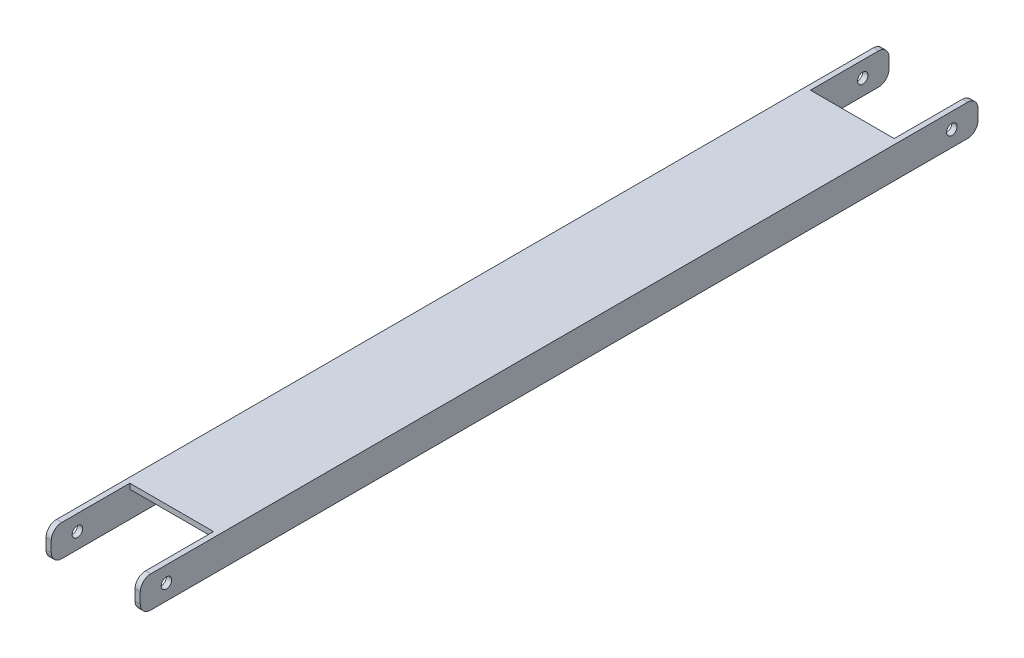
SolidWorks part; units mm, degrees
ref_plane "Front Plane" through (0, 0, 0) normal (0, 0, 1) x (1, 0, 0)
ref_plane "Top Plane" through (0, 0, 0) normal (0, 1, 0) x (1, 0, 0)
ref_plane "Right Plane" through (0, 0, 0) normal (1, 0, 0) x (0, 0, -1)
sketch "Sketch1" plane through (0, 0, 0) normal (0, 0, 1) x (1, 0, 0)
  line L0 (8, -3) -> (8, 2)
  line L2 (9, -3) -> (9, 3)
  line L3 (9, 3) -> (-9, 3)
  line L4 (-9, -3) -> (-9, 3)
  line L5 (9, -3) -> (-9, 3) construction
  line L6 (9, 3) -> (-9, -3) construction
  line L7 (8, 2) -> (-8, 2)
  line L8 (-8, -3) -> (-8, 2)
  line L9 (-9, -3) -> (-8, -3)
  line L10 (8, -3) -> (9, -3)
  point P0 (0, 0)
  dimension "D1" = 18
  dimension "D2" = 6
  dimension "D3" = 1
extrude "Boss-Extrude1" add sketch "Sketch1" along normal blind 160
sketch "Sketch3" plane through (0, 3, 0) normal (0, 1, 0) x (1, 0, 0)
  line L0 (-8, 0) -> (8, 0)
  line L1 (9, 0) -> (-9, 0) construction
  line L2 (-8, 0) -> (-8, -15)
  line L3 (-8, -15) -> (8, -15)
  line L4 (8, -15) -> (8, 0)
  line L5 (-9, -80) -> (9, -80) construction
  line L6 (-9, -160) -> (-9, 0) construction
  line L7 (9, -160) -> (9, 0) construction
  dimension "D1" = 16
  dimension "D2" = 1
  dimension "D3" = 15
extrude "Cut-Extrude1" cut sketch "Sketch3" against normal through all contours L3 L4 L0 L2
sketch "Sketch4" plane through (0, 3, 0) normal (0, 1, 0) x (1, 0, 0)
  line L0 (9, -80) -> (-9, -80) construction
  line L1 (9, -160) -> (9, 0) construction
  line L2 (-9, -160) -> (-9, 0) construction
  line L3 (-8, -160) -> (-8, -145)
  line L12 (-8, -145) -> (8, -145)
  line L13 (8, -145) -> (8, -160)
  line L14 (8, -160) -> (-8, -160)
extrude "Cut-Extrude2" cut sketch "Sketch4" against normal through all
sketch "Sketch5" plane through (9, 0, 0) normal (1, 0, 0) x (0, 0, -1)
  line L0 (-160, -3) -> (-160, 3) construction
  line L1 (0, -3) -> (0, 3) construction
  circle A0 centre (-155, 0) radius 1
  circle A1 centre (-5, 0) radius 1
  dimension "D1" = 2
  dimension "D2" = 2
  dimension "D4" = 5
  dimension "D3" = 5
extrude "Cut-Extrude3" cut sketch "Sketch5" against normal through all
fillet "Fillet1" radius 2 8 edges at (8.5, -3, 0) (8.5, 3, 0) (-8.5, 3, 0) (-8.5, -3, 0) (-8.5, -3, 160) (-8.5, 3, 160) (8.5, -3, 160) (8.5, 3, 160)
